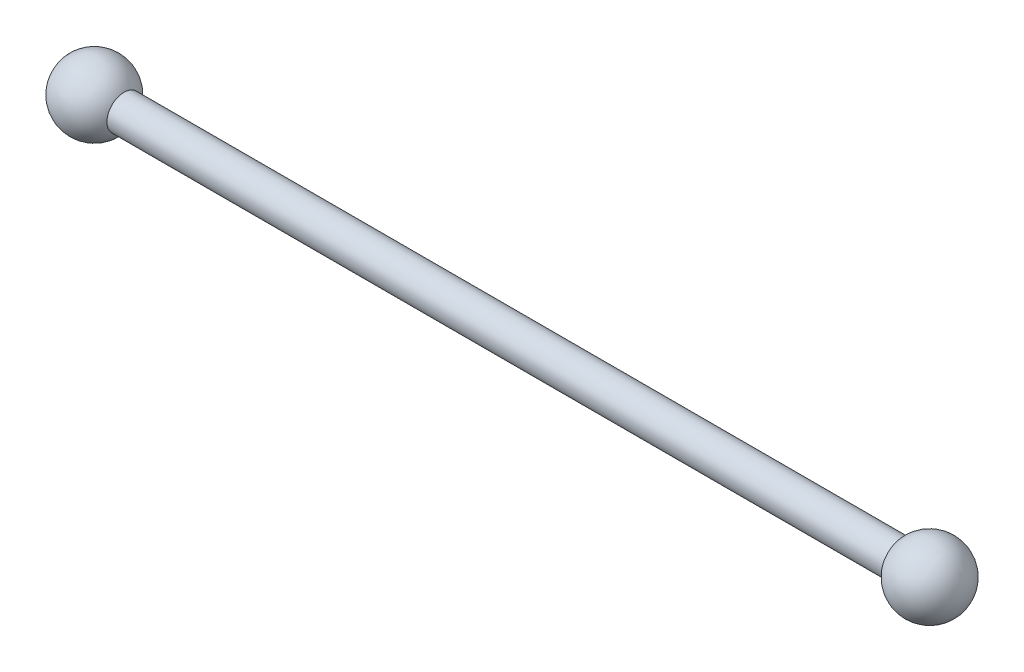
SolidWorks part; units mm, degrees
material "Cast Alloy Steel"
ref_plane "Front Plane" through (0, 0, 0) normal (0, 0, 1) x (1, 0, 0)
ref_plane "Top Plane" through (0, 0, 0) normal (0, 1, 0) x (1, 0, 0)
ref_plane "Right Plane" through (0, 0, 0) normal (1, 0, 0) x (0, 0, -1)
sketch "Sketch1" plane through (0, 0, 0) normal (0, 0, 1) x (1, 0, 0)
  line L0 (17.25, -0.75) -> (22.25, -0.75) construction
  line L1 (-17.25, 0.75) -> (17.25, 0.75)
  line L2 (-17.25, 0.75) -> (-17.25, -0.75)
  line L3 (-17.25, -0.75) -> (17.25, -0.75)
  line L4 (17.25, 0.75) -> (17.25, -0.75)
  line L5 (-17.25, 0.75) -> (17.25, -0.75) construction
  line L6 (-17.25, -0.75) -> (17.25, 0.75) construction
  line L7 (17.25, -0.75) -> (22.25, -0.75)
  arc A2 (22.25, -0.75) -> (16.6519, 0.75) centre (19.25, -0.75) ccw
  point P0 (0, 0)
  dimension "D4" = 3
  dimension "D1" = 1.5
  dimension "D2" = 34.5
  dimension "D3" = 5
revolve "Revolve1" add sketch "Sketch1" angle 360 about L3
mirror "Mirror1" about plane through (-17.25, 0, 0) normal (1, 0, 0) of "Revolve1"
